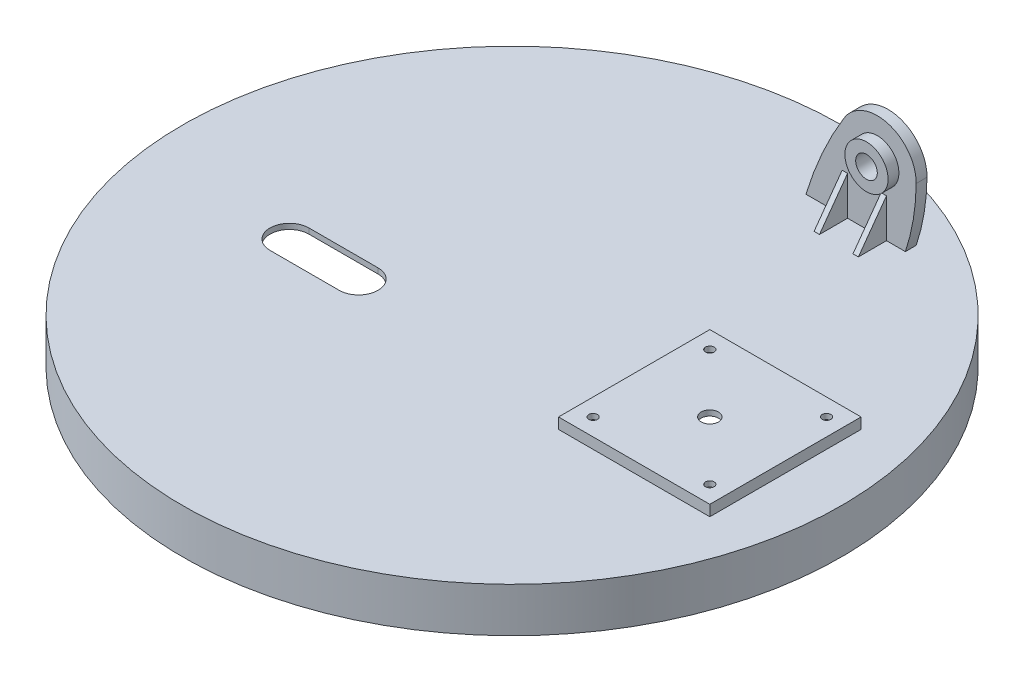
SolidWorks part; units mm, degrees
ref_plane "前视基准面" through (0, 0, 0) normal (0, 0, 1) x (1, 0, 0)
ref_plane "上视基准面" through (0, 0, 0) normal (0, 1, 0) x (1, 0, 0)
ref_plane "右视基准面" through (0, 0, 0) normal (1, 0, 0) x (0, 0, -1)
other "Configuration Table"
sketch "草图1" plane through (0, 0, 0) normal (0, 1, 0) x (1, 0, 0)
  circle A0 centre (0, 0) radius 305
  dimension "D1" = 610
extrude "凸台-拉伸1" add sketch "草图1" along normal blind 41.2
sketch "草图2" plane through (0, 41.2, 0) normal (0, 1, 0) x (1, 0, 0)
  line L1 (253, -70) -> (113, -70)
  line L2 (253, -70) -> (253, 70)
  line L3 (253, 70) -> (113, 70)
  line L4 (113, -70) -> (113, 70)
  line L5 (253, -70) -> (113, 70) construction
  line L6 (253, 70) -> (113, -70) construction
  point P0 (183, 0)
  dimension "D1" = 140
  dimension "D2" = 113
extrude "凸台-拉伸2" add sketch "草图2" along normal blind 10
shell "抽壳1" thickness 5
sketch "草图3" plane through (0, 41.2, 0) normal (0, 1, 0) x (1, 0, 0)
  line L0 (-164, -42) -> (-100, -42) construction
  line L1 (-164, -24) -> (-100, -24)
  line L2 (-164, -60) -> (-100, -60)
  arc A0 (-164, -24) -> (-164, -60) centre (-164, -42) ccw
  arc A1 (-100, -60) -> (-100, -24) centre (-100, -42) ccw
  point P2 (-132, -42)
  dimension "D1" = 100
  dimension "D4" = 100
  dimension "D2" = 36
  dimension "D3" = 42
extrude "切除-拉伸1" cut sketch "草图3" against normal blind 10
sketch "草图4" plane through (0, 41.2, 0) normal (0, 1, 0) x (1, 0, 0)
  line L1 (39, 243) -> (159, 243)
  line L2 (39, 243) -> (39, 233)
  line L3 (39, 233) -> (159, 233)
  line L4 (159, 243) -> (159, 233)
  dimension "D1" = 39
  dimension "D2" = 243
  dimension "D3" = 10
  dimension "D4" = 120
extrude "凸台-拉伸3" add sketch "草图4" along normal blind 150
sketch "草图5" plane through (0, 0, -233) normal (0, 0, 1) x (1, 0, 0)
  line L0 (39, 41.2) -> (159, 41.2) construction
  line L2 (131, 41.2) -> (159, 41.2)
  line L3 (159, 41.2) -> (159, 191.2)
  line L4 (159, 191.2) -> (39, 191.2)
  line L5 (39, 191.2) -> (39, 41.2)
  arc A0 (39, 41.2) -> (74.3103, 120.0187) centre (360.7475, -55.6222) cw
  arc A1 (74.3103, 120.0187) -> (140.998, 100.8218) centre (105, 101.2) cw
  arc A2 (140.998, 100.8218) -> (131, 41.2) centre (-53.9912, 102.8705) cw
  dimension "D1" = 105
  dimension "D2" = 336
  dimension "D3" = 195
  dimension "D6" = 36
  dimension "D4" = 92
  dimension "D5" = 60
extrude "切除-拉伸3" cut sketch "草图5" against normal through all
sketch "草图6" plane through (0, 0, -233) normal (0, 0, 1) x (1, 0, 0)
  circle A1 centre (105, 101.2) radius 10
  dimension "D1" = 20
extrude "切除-拉伸5" cut sketch "草图6" against normal through all
sketch "草图7" plane through (0, 0, -233) normal (0, 0, 1) x (1, 0, 0)
  circle A0 centre (105, 101.2) radius 20
  circle A1 centre (105, 101.2) radius 10 construction
  circle A2 centre (105, 101.2) radius 10
  dimension "D1" = 40
extrude "凸台-拉伸4" add sketch "草图7" along normal blind 10
sketch "草图8" plane through (0, 0, -233) normal (0, 0, 1) x (1, 0, 0)
  line L0 (305, 41.2) -> (-305, 41.2) construction
  line L1 (72.5, 41.2) -> (77.5, 41.2)
  line L2 (72.5, 41.2) -> (72.5, 77.2)
  line L3 (72.5, 77.2) -> (77.5, 77.2)
  line L4 (77.5, 41.2) -> (77.5, 77.2)
  line L6 (108.5, 41.2) -> (113.5, 41.2)
  line L7 (108.5, 41.2) -> (108.5, 77.2)
  line L8 (108.5, 77.2) -> (113.5, 77.2)
  line L9 (113.5, 41.2) -> (113.5, 77.2)
  point P10 (75, 41.2)
  point P12 (111, 41.2)
  dimension "D1" = 75
  dimension "D2" = 36
  dimension "D3" = 36
  dimension "D4" = 5
extrude "凸台-拉伸5" add sketch "草图8" along normal blind 26
sketch "草图9" plane through (113.5, 0, 0) normal (1, 0, 0) x (0, 0, -1)
  line L0 (207, 41.2) -> (233, 77.2)
  line L1 (233, 77.2) -> (207, 77.2)
  line L2 (207, 77.2) -> (207, 41.2)
extrude "切除-拉伸6" cut sketch "草图9" against normal through all
sketch "草图10" plane through (0, 0, 0) normal (0, 0, 1) x (1, 0, 0)
  line L0 (-80, -10.3) -> (-85, -10.3)
  line L1 (-85, -10.3) -> (-85, 36.2)
  line L2 (-85, 36.2) -> (-80, 36.2)
  line L3 (-80, 36.2) -> (-80, -10.3)
  line L4 (-75, 36.2) -> (-75, 31.2)
  line L5 (-75, 31.2) -> (-56, 31.2)
  line L6 (-56, 31.2) -> (-56, 36.2)
  line L7 (-56, 36.2) -> (-75, 36.2)
  line L9 (0, 0) -> (0, 41.2) construction
  line L10 (305, 41.2) -> (-305, 41.2) construction
  dimension "D1" = 5
  dimension "D2" = 150
  dimension "D3" = 170
  dimension "D4" = 5
  dimension "D5" = 19
  dimension "D6" = 5
  dimension "D7" = 51.5
revolve "旋转1" add sketch "草图10" angle 360 about L9
sketch "草图11" plane through (0, 51.2, 0) normal (0, 1, 0) x (1, 0, 0)
  line L1 (237, -54) -> (129, -54) construction
  line L2 (237, -54) -> (237, 54) construction
  line L3 (237, 54) -> (129, 54) construction
  line L4 (129, -54) -> (129, 54) construction
  line L5 (237, -54) -> (129, 54) construction
  line L6 (237, 54) -> (129, -54) construction
  circle A0 centre (183, 0) radius 8
  circle A1 centre (237, 54) radius 4
  circle A2 centre (129, 54) radius 4
  circle A3 centre (129, -54) radius 4
  circle A4 centre (237, -54) radius 4
  point P0 (183, 0)
  dimension "D2" = 8
  dimension "D3" = 16
  dimension "D1" = 108
extrude "切除-拉伸7" cut sketch "草图11" against normal through all
